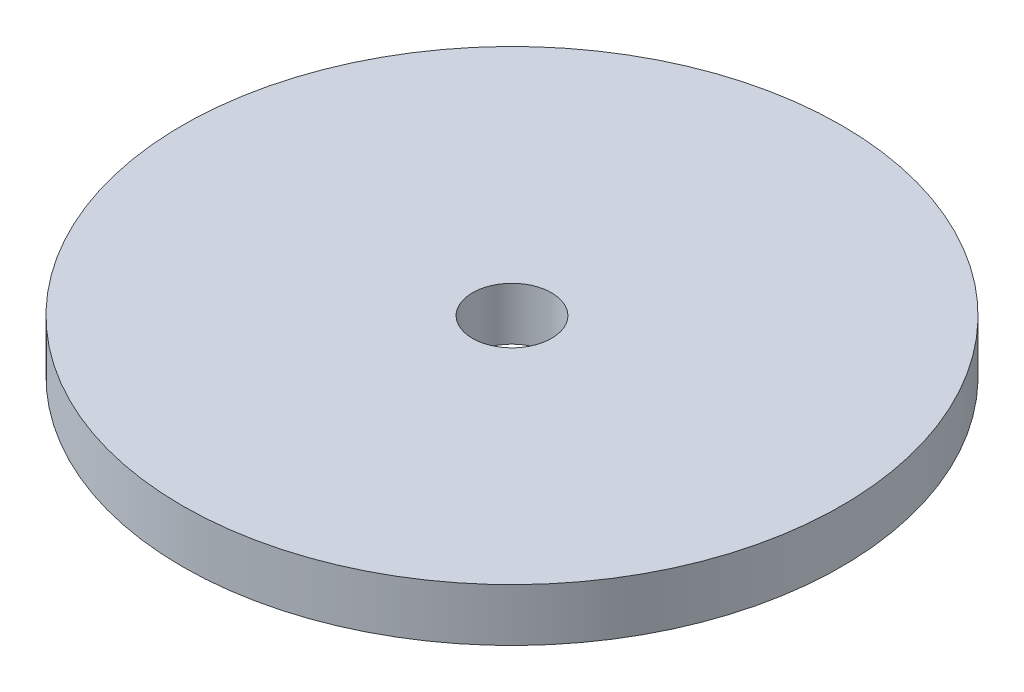
SolidWorks part; units mm, degrees
ref_plane "前视基准面" through (0, 0, 0) normal (0, 0, 1) x (1, 0, 0)
ref_plane "上视基准面" through (0, 0, 0) normal (0, 1, 0) x (1, 0, 0)
ref_plane "右视基准面" through (0, 0, 0) normal (1, 0, 0) x (0, 0, -1)
sketch "Sketch1" plane through (0, 0, 0) normal (0, 1, 0) x (1, 0, 0)
  circle A0 centre (0, 0) radius 12.5
  circle A1 centre (0, 0) radius 1.5
  dimension "D1" = 3
  dimension "D2" = 25
extrude "Boss-Extrude1" add sketch "Sketch1" along normal blind 2
